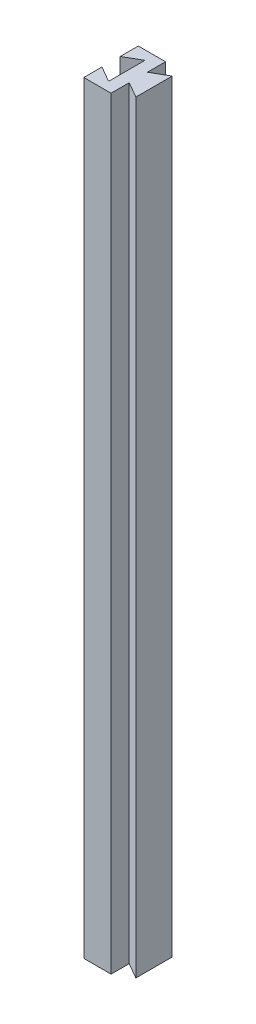
SolidWorks part; units mm, degrees
ref_plane "Front Plane" through (0, 0, 0) normal (0, 0, 1) x (1, 0, 0)
ref_plane "Top Plane" through (0, 0, 0) normal (0, 1, 0) x (1, 0, 0)
ref_plane "Right Plane" through (0, 0, 0) normal (1, 0, 0) x (0, 0, -1)
sketch "Sketch1" plane through (0, 0, 0) normal (0, 1, 0) x (1, 0, 0)
  line L0 (-33.0953, 6.9672) -> (-33.0953, -1.4995)
  line L1 (-45.7953, -18.4328) -> (-33.0953, -18.4328)
  line L2 (-33.0953, -18.4328) -> (-33.0953, -9.9662)
  line L3 (-33.0953, 6.9672) -> (-45.7953, 6.9672)
  line L4 (-33.0953, -9.9662) -> (-25.763, -14.1995)
  line L5 (-33.0953, -1.4995) -> (-25.763, 2.7338)
  line L6 (-25.763, 2.7338) -> (-25.763, -14.1995)
  line L7 (-45.7953, 6.9672) -> (-45.7953, -1.4995)
  line L8 (-45.7953, -9.9662) -> (-38.463, -14.1995)
  line L9 (-38.463, -14.1995) -> (-38.463, 2.7338)
  line L10 (-38.463, 2.7338) -> (-45.7953, -1.4995)
  line L11 (-45.7953, -9.9662) -> (-45.7953, -18.4328)
  dimension "D1" = 8.4667
  dimension "D2" = 8.4667
  dimension "D3" = 16.9333
  dimension "D4" = 16.9333
  dimension "D5" = 12.7
  dimension "D6" = 8.4667
  dimension "D7" = 8.4667
  dimension "D8" = 25.4
  dimension "D9" = 8.4667
  dimension "D10" = 8.4667
  dimension "D11" = 8.4667
  dimension "D12" = 8.4667
extrude "Boss-Extrude1" add sketch "Sketch1" along normal blind 355.6
